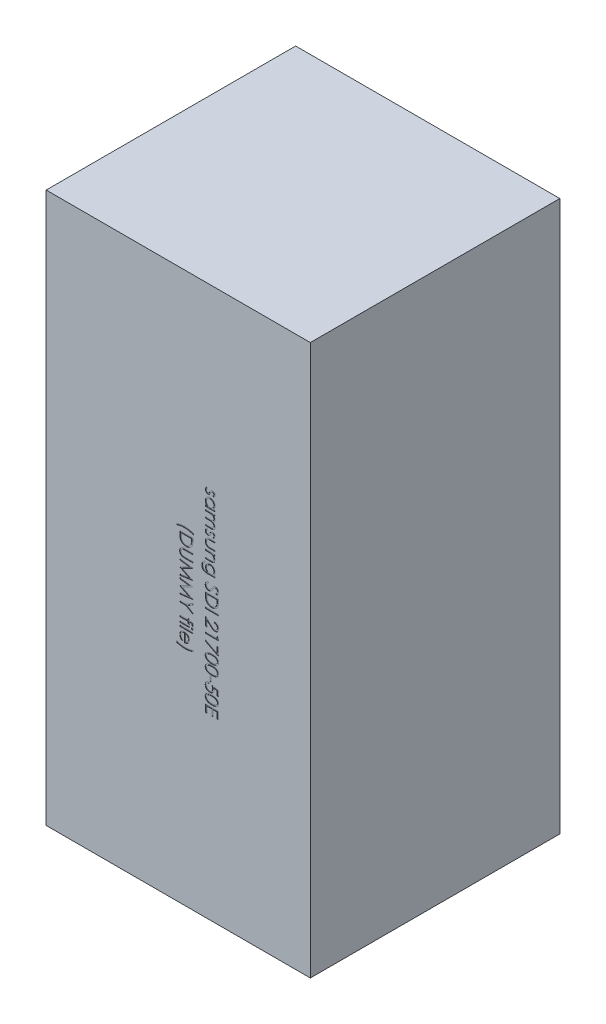
SolidWorks part; units mm, degrees
ref_plane "정면" through (0, 0, 0) normal (0, 0, 1) x (1, 0, 0)
ref_plane "윗면" through (0, 0, 0) normal (0, 1, 0) x (1, 0, 0)
ref_plane "우측면" through (0, 0, 0) normal (1, 0, 0) x (0, 0, -1)
sketch "스케치1" plane through (0, 0, 0) normal (0, 0, 1) x (1, 0, 0)
  line L1 (-36, 75) -> (36, 75)
  line L2 (-36, 75) -> (-36, -75)
  line L3 (-36, -75) -> (36, -75)
  line L4 (36, 75) -> (36, -75)
  line L5 (-36, 75) -> (36, -75) construction
  line L6 (-36, -75) -> (36, 75) construction
  point P0 (0, 0)
  dimension "D1" = 150
  dimension "D2" = 72
extrude "보스-돌출1" add sketch "스케치1" along normal blind 68
sketch "스케치2" plane through (0, 0, 68) normal (0, 0, 1) x (1, 0, 0)
  line L0 (7.439, 75) -> (7.439, -75) construction
  line L1 (36, 75) -> (-36, 75) construction
  line L2 (-36, -75) -> (36, -75) construction
  text T0 "samsung SDI 21700-50E\r\n(DUMMY file)"
extrude "컷-돌출1" cut sketch "스케치2" against normal blind 0.1
